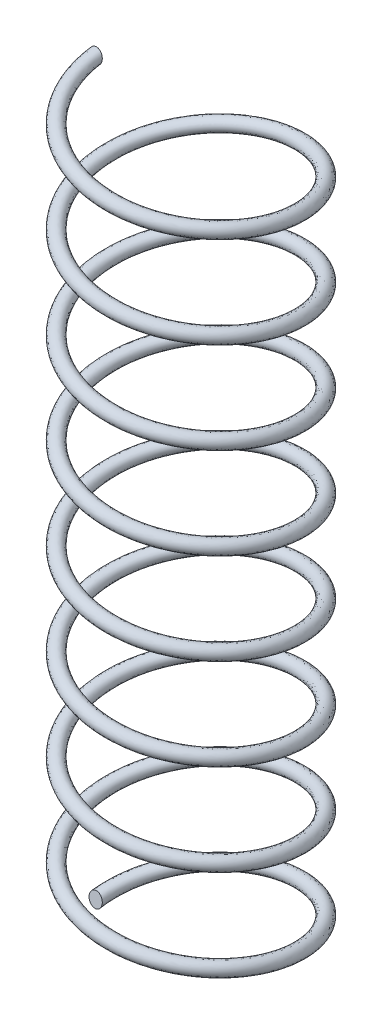
SolidWorks part; units mm, degrees
ref_plane "Front Plane" through (0, 0, 0) normal (0, 0, 1) x (1, 0, 0)
ref_plane "Top Plane" through (0, 0, 0) normal (0, 1, 0) x (1, 0, 0)
ref_plane "Right Plane" through (0, 0, 0) normal (1, 0, 0) x (0, 0, -1)
sketch "Sketch1" plane through (0, 0, 0) normal (0, 1, 0) x (1, 0, 0)
  circle A0 centre (0, 0) radius 3.429
  dimension "D1" = 6.858
curve "Helix/Spiral1" pitch 3.2861 height 26.289 turns 8
ref_plane "Plane1" through (-3.429, 26.289, 0) normal (0, 0.1508, -0.9886) x (-1, 0, 0)
sketch "Sketch2" plane through (-3.429, 26.289, 0) normal (0, 0.1508, -0.9886) x (-1, 0, 0)
  circle A0 centre (-6.8483, -1.7017) radius 0.254
  dimension "D1" = 0.508
sweep "Sweep1" add profiles "Sketch2" path "Helix/Spiral1"
sketch "Sketch3" plane through (0, 0, 0) normal (1, 0, 0) x (0, 0, -1)
  line L0 (0, 32.6783) -> (0, -5.4557) construction
sketch "Sketch4" plane through (0, 0, 0) normal (0, 0, 1) x (1, 0, 0)
  line L0 (0, 37.4284) -> (0, -17.0166)
